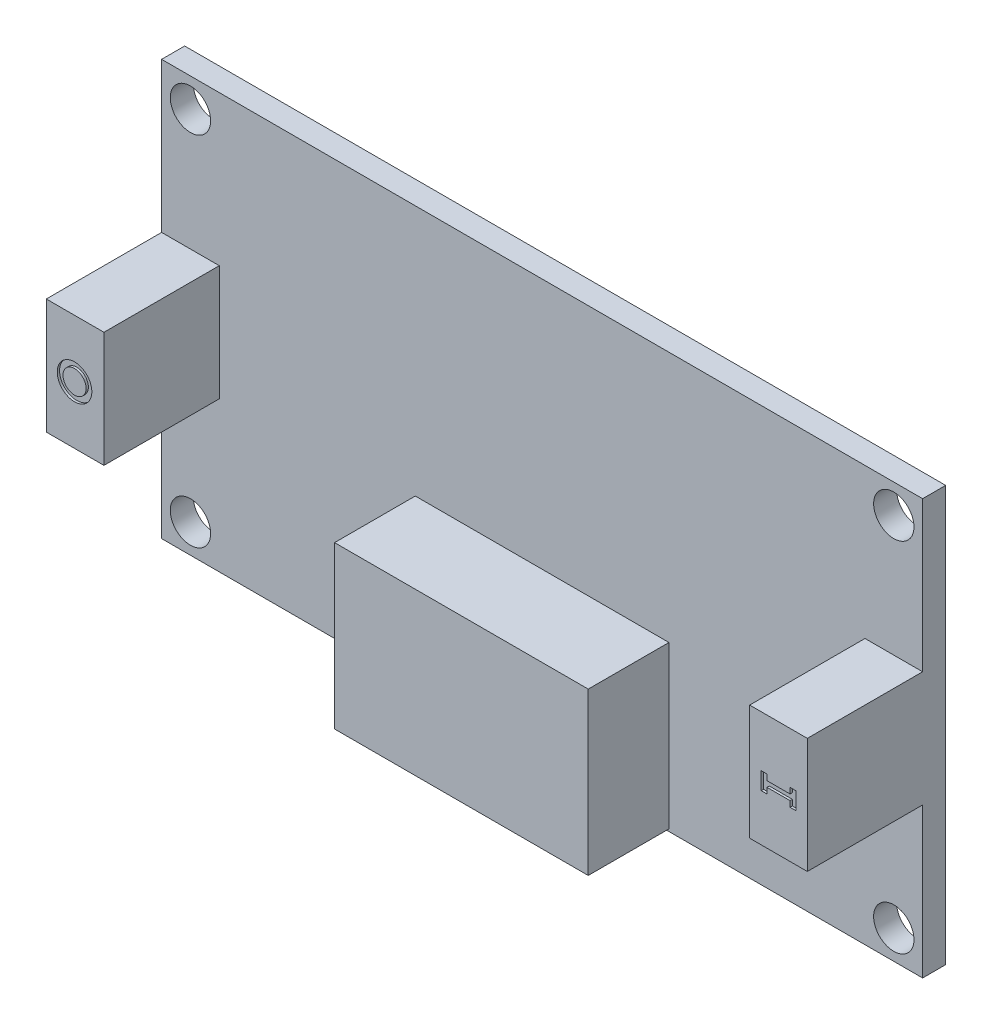
SolidWorks part; units mm, degrees
ref_plane "前视基准面" through (0, 0, 0) normal (0, 0, 1) x (1, 0, 0)
ref_plane "上视基准面" through (0, 0, 0) normal (0, 1, 0) x (1, 0, 0)
ref_plane "右视基准面" through (0, 0, 0) normal (1, 0, 0) x (0, 0, -1)
sketch "草图1" plane through (0, 0, 0) normal (0, 0, 1) x (1, 0, 0)
  line L0 (0, 0) -> (50.9426, 0) construction
  line L1 (-33, -18) -> (33, -18)
  line L2 (-33, -18) -> (-33, 18)
  line L3 (-33, 18) -> (33, 18)
  line L4 (33, -18) -> (33, 18)
  line L5 (-33, -18) -> (33, 18) construction
  line L6 (-33, 18) -> (33, -18) construction
  line L7 (0, 0) -> (0, 23.973) construction
  circle A0 centre (30.5, 15.5) radius 1.75
  circle A1 centre (30.5, -15.5) radius 1.75
  circle A2 centre (-30.5, -15.5) radius 1.75
  circle A3 centre (-30.5, 15.5) radius 1.75
  point P0 (0, 0)
  dimension "D5" = 3.5
  dimension "D1" = 31
  dimension "D2" = 61
  dimension "D3" = 36
  dimension "D4" = 66
extrude "凸台-拉伸1" add sketch "草图1" along normal blind 2
sketch "草图2" plane through (0, 0, 2) normal (0, 0, 1) x (1, 0, 0)
  line L0 (-33, -18) -> (33, -18) construction
  line L1 (-11, -17.8) -> (11, -17.8)
  line L2 (-11, -17.8) -> (-11, -3.8)
  line L3 (-11, -3.8) -> (11, -3.8)
  line L4 (11, -17.8) -> (11, -3.8)
  line L5 (-11, -17.8) -> (11, -3.8) construction
  line L6 (-11, -3.8) -> (11, -17.8) construction
  line L7 (-33, 18) -> (-33, -18) construction
  point P0 (0, -10.8)
  dimension "D1" = 14
  dimension "D2" = 22
  dimension "D3" = 7.2
  dimension "D4" = 33
extrude "凸台-拉伸2" add sketch "草图2" along normal blind 7
sketch "草图3" plane through (0, 0, 2) normal (0, 0, 1) x (1, 0, 0)
  line L0 (33, -18) -> (33, 18) construction
  line L1 (-33, 5) -> (-28, 5)
  line L2 (-33, 5) -> (-33, -5)
  line L3 (-33, -5) -> (-28, -5)
  line L4 (-28, 5) -> (-28, -5)
  line L5 (-33, 5) -> (-28, -5) construction
  line L6 (-33, -5) -> (-28, 5) construction
  line L7 (28, 5) -> (33, 5)
  line L8 (28, 5) -> (28, -5)
  line L9 (28, -5) -> (33, -5)
  line L10 (33, 5) -> (33, -5)
  line L11 (28, 5) -> (33, -5) construction
  line L12 (28, -5) -> (33, 5) construction
  line L13 (-33, 18) -> (-33, -18) construction
  point P0 (-30.5, 0)
  point P5 (30.5, 0)
  dimension "D1" = 5
  dimension "D2" = 10
  dimension "D3" = 10
  dimension "D4" = 5
extrude "凸台-拉伸3" add sketch "草图3" along normal blind 10
sketch "草图4" plane through (0, 0, 12) normal (0, 0, 1) x (1, 0, 0)
  line L0 (29, 0.5714) -> (29, -0.9286)
  line L1 (29, -0.9286) -> (29.5, -0.9286)
  line L2 (29.5, -0.9286) -> (29.5, -0.4286)
  line L3 (29.5, -0.4286) -> (31.5, -0.4286)
  line L4 (31.5, -0.4286) -> (31.5, -0.9286)
  line L5 (31.5, -0.9286) -> (32, -0.9286)
  line L6 (32, -0.9286) -> (32, 0.5714)
  line L7 (32, 0.5714) -> (31.5, 0.5714)
  line L8 (31.5, 0.5714) -> (31.5, 0.0714)
  line L9 (31.5, 0.0714) -> (29.5, 0.0714)
  line L10 (29.5, 0.0714) -> (29.5, 0.5714)
  line L11 (29.5, 0.5714) -> (29, 0.5714)
  line L12 (33, -5) -> (33, 5) construction
  dimension "D1" = 0.5
  dimension "D2" = 0.5
  dimension "D3" = 0.5
  dimension "D4" = 0.5
  dimension "D5" = 2
  dimension "D6" = 0.5
  dimension "D7" = 1
extrude "切除-拉伸1" cut sketch "草图4" against normal blind 0.2
sketch "草图5" plane through (0, 0, 12) normal (0, 0, 1) x (1, 0, 0)
  circle A0 centre (-30.5516, 0) radius 1
  circle A1 centre (-30.5516, 0) radius 1.5
  dimension "D1" = 2
  dimension "D2" = 3
extrude "切除-拉伸2" cut sketch "草图5" against normal blind 0.2
